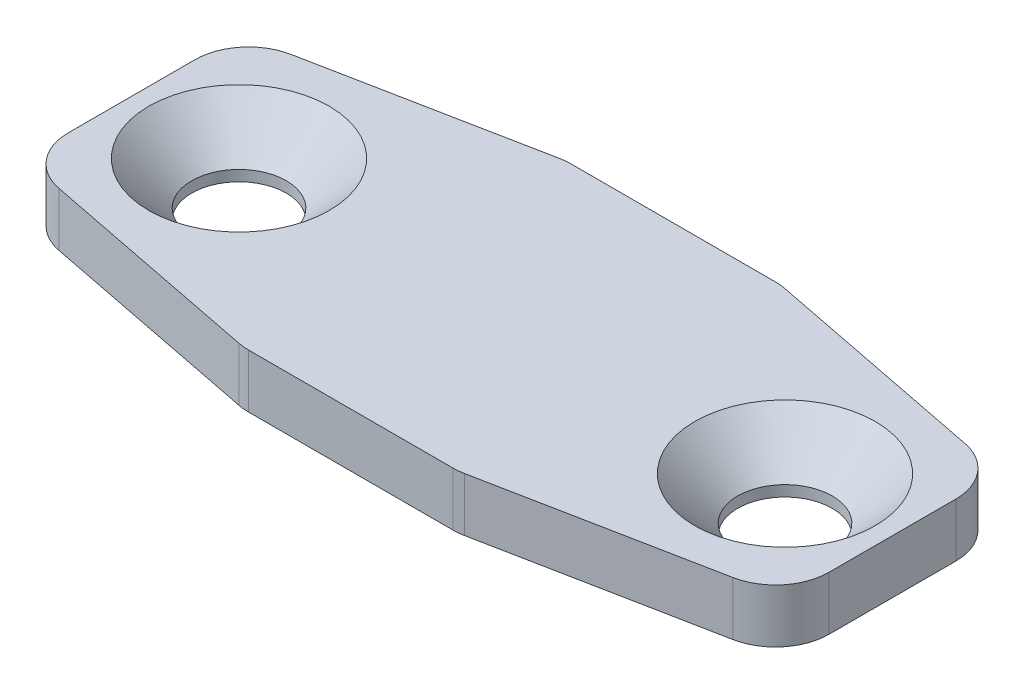
SolidWorks part; units mm, degrees
ref_plane "Front Plane" through (0, 0, 0) normal (0, 0, 1) x (1, 0, 0)
ref_plane "Top Plane" through (0, 0, 0) normal (0, 1, 0) x (1, 0, 0)
ref_plane "Right Plane" through (0, 0, 0) normal (1, 0, 0) x (0, 0, -1)
sketch "Sketch1" plane through (0, 0, 0) normal (0, 1, 0) x (1, 0, 0)
  line L0 (-2.9334, 0) -> (-32.947, 0) construction
  line L1 (-17.7, -5) -> (-5, -7.5)
  line L2 (-5, -7.5) -> (5, -7.5)
  line L3 (0, -10.1369) -> (0, 0) construction
  line L4 (-17.7, 5) -> (-17.7, -5)
  line L5 (-17.7, 5) -> (-5, 7.5)
  line L6 (-5, 7.5) -> (5, 7.5)
  line L7 (17.7, -5) -> (5, -7.5)
  line L8 (17.7, 5) -> (17.7, -5)
  line L9 (17.7, 5) -> (5, 7.5)
  point P11 (-17.7, 0)
  point P14 (0, -7.5)
  point P17 (0, 7.5)
  dimension "D1" = 5
  dimension "D2" = 7.5
  dimension "D3" = 17.7
  dimension "D4" = 5
extrude "Boss-Extrude1" add sketch "Sketch1" along normal blind 2.5
sketch "Sketch2" plane through (0, 2.5, 0) normal (0, 1, 0) x (1, 0, 0)
  line L0 (0, 11.7152) -> (0, -15.7093) construction
  line L1 (-21.1961, 0) -> (25.5716, 0) construction
  circle A0 centre (-12.7, 0) radius 2.2
  circle A1 centre (12.7, 0) radius 2.2
  dimension "D1" = 4.4
  dimension "D2" = 4.4
  dimension "D3" = 12.7
  dimension "D4" = 12.7
extrude "Cut-Extrude2" cut sketch "Sketch2" against normal up to next
chamfer "Chamfer1" distance 2 angle 45 2 edges at (12.7, 2.5, 2.2) (-12.7, 2.5, 2.2)
fillet "Fillet1" radius 2.5 8 edges at (-5, 1.25, 7.5) (5, 1.25, 7.5) (17.7, 1.25, 5) (17.7, 1.25, -5) (5, 1.25, -7.5) (-5, 1.25, -7.5) (-17.7, 1.25, -5) (-17.7, 1.25, 5)
